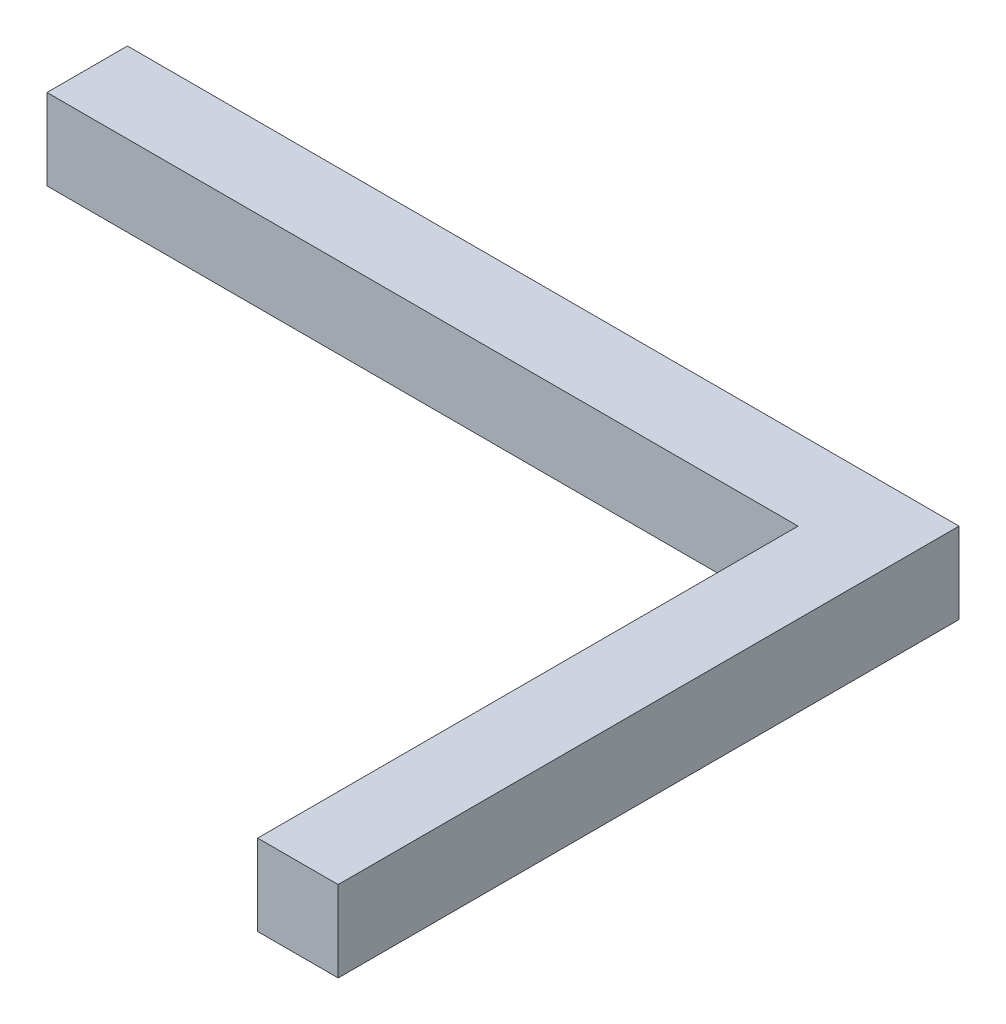
SolidWorks part; units mm, degrees
ref_plane "Front Plane" through (0, 0, 0) normal (0, 0, 1) x (1, 0, 0)
ref_plane "Top Plane" through (0, 0, 0) normal (0, 1, 0) x (1, 0, 0)
ref_plane "Right Plane" through (0, 0, 0) normal (1, 0, 0) x (0, 0, -1)
sketch "Sketch1" plane through (0, 0, 0) normal (0, 1, 0) x (1, 0, 0)
  line L1 (0, 0) -> (49.6, 0)
  line L2 (0, 0) -> (0, 49.6)
  line L3 (0, 49.6) -> (49.6, 49.6)
  line L4 (49.6, 0) -> (49.6, 49.6)
  line L5 (0, 0) -> (49.6, 49.6) construction
  line L6 (0, 49.6) -> (49.6, 0) construction
  point P4 (24.8, 24.8)
  dimension "D1" = 49.6
  dimension "D2" = 49.6
extrude "Boss-Extrude1" add sketch "Sketch1" along normal blind 4.826
sketch "Sketch2" plane through (0, 4.826, 0) normal (0, 1, 0) x (1, 0, 0)
  line L5 (8.1217, 49.6) -> (8.1217, 44.8) construction
  line L6 (0, 0) -> (44.8, 0)
  line L7 (0, 0) -> (0, 44.8)
  line L9 (0, 44.8) -> (44.8, 44.8)
  line L11 (44.8, 0) -> (44.8, 44.8)
  line L12 (0, 0) -> (44.8, 44.8) construction
  line L13 (0, 44.8) -> (44.8, 0) construction
  line L14 (49.6, 49.6) -> (0, 49.6) construction
  point P4 (22.4, 22.4)
  dimension "D1" = 4.8
  dimension "D2" = 44.8
extrude "Cut-Extrude1" cut sketch "Sketch2" against normal through all
ref_plane "Plane1" through (0, 2.413, 0) normal (0, -1, 0) x (-1, 0, 0)
ref_plane "Plane2" through (0, 0, -24.8) normal (0, 0, -1) x (-1, 0, 0)
ref_plane "Plane3" through (0, 0, -47.2) normal (0, 0, 1) x (1, 0, 0)
ref_point "Point1"
ref_plane "Plane5" through (47.2, 0, 0) normal (1, 0, 0) x (0, 0, -1)
ref_plane "Plane6" through (0, 2.413, 0) normal (0, 1, 0) x (1, 0, 0)
sketch "Sketch6" plane through (49.6, 0, 0) normal (1, 0, 0) x (0, 0, -1)
  line L1 (0, 0) -> (49.6, 0) construction
  line L2 (0, 4.826) -> (12.57, 4.826)
  line L3 (0, 4.826) -> (0, 0)
  line L4 (0, 0) -> (12.57, 0)
  line L5 (12.57, 4.826) -> (12.57, 0)
  line L6 (0, 4.826) -> (12.57, 0) construction
  line L7 (0, 0) -> (12.57, 4.826) construction
  line L8 (12.57, 15.113) -> (12.57, -10.287) construction
  point P8 (6.285, 2.413)
extrude "Cut-Extrude2" cut sketch "Sketch6" against normal through all
ref_point "Point3"
equation "\"MDF\"= 4.8mm"
equation "\"Foamcore\"= 4.6mm"
equation "\"GMaterial\"= \"MDF\""
equation "\"PCB\" = 1.6mm"
equation "\"BaseWidth\" = 10in"
equation "\"SkidLength\" = 1in"
equation "\"SkidClearance\" = 0.4in"
equation "\"MotorMountLength\" = 2in"
equation "\"MotorMountWidth\" = \"GMaterial\""
equation "\"MotorMountHeight\" = 2.25in"
equation "\"UnoStackWidth\" = 77.4mm"
equation "\"UnoStackLength\" = 79.8mm"
equation "\"UnoStackHeight\" = 34.2mm"
equation "\"TallHexRiserHeight\" = 22.2mm"
equation "\"PingPongBallSize\" = 40mm"
equation "\"BarrelLength\" = 9in"
equation "\"BarrelSize\" = \"PingPongBallSize\""
equation "\"PlatformLength\" = 4in"
equation "\"PlatformWidth\" = 6in"
equation "\"WheelDiameter\"=2.99213"
equation "\"ServoMountHeight\"=2.49223"
equation "\"ServoGearHeight\" = 0.95330261in"
equation "\"ServoMountLength\"= 1.53774"
equation "\"PivotHoleRadius\"= 0.616358"
equation "\"PlatformMountHeight\" = 3.19"
equation "\"TensionOffSet\"= .3mm"
equation "\"MotorMountWedge\"=0.333333"
equation "\"LaserCutterOffset\"= .3mm"
equation "\"BumperWidth\"=11"
equation "\"PitcherWheelCompression\" = 2.5mm"
equation "\"PitchingWheelWidth\" = 26.2mm"
equation "\"PitchingWheelDiameter\" = 65.5mm"
equation "\"PitchingWheelMountOffset\" = 8.4mm"
equation "\"PitchingWheelInnerDiameter\" = 45.5mm"
equation "\"PitchingWheelBoltShoulder\" = 4.5mm"
equation "\"BrassCouplingLength\" = 18mm"
equation "\"PitchingMotorHeight\" = 57.0mm"
equation "\"PitchingMotorShaftTopHeight\" = \"PitchingMotorHeight\" - 44.1mm"
equation "\"PitchingMotorBodyHeight\" = 38mm"
equation "\"PitchingMotorTopShoulderHeight\" = 40.6mm - \"PitchingMotorBodyHeight\" "
equation "\"PitchingMotorBottomShoulderHeight\" = 40.2mm - \"PitchingMotorBodyHeight\""
equation "\"PitchingMotorBottomShaftHeight\" = \"PitchingMotorHeight\" - \"PitchingMotorShaftTopHeight\" - \"PitchingMotorTopShoulderHeight\" - \"PitchingMotorBodyHeight\" - \"PitchingMotorBottomShoulderHeight\""
equation "\"PitchingMotorShaftDiameter\" = 2.2mm"
equation "\"PitchingMotorBodyDiameter\" = 27.4mm"
equation "\"PitchingMotorTopShoulderDiameter\" = 9.8mm"
equation "\"PitchingMotorBottomShoulderDiameter\" = 9.8mm"
equation "\"BrassCouplingHexSize\" = 12mm"
equation "\"BrassCouplingBoreSize\" = 3.17mm"
equation "\"PitchingMotorMountingHoleDistance\" = 16mm"
equation "\"Acrylic\" = 4.4mm"
equation "\"PitchingMotorDistance\" = \"PitchingWheelDiameter\" + \"PingPongBallSize\" - \"PitcherWheelCompression\"*2"
equation "\"PitchingMotorPlatformOffset\"=1"
equation "\"ServoPlatformOffset\"=1.64173"
equation "\"BallBearingDiameter\" = 22mm"
equation "\"BallBearingWidth\" = 9mm"
equation "\"BallBearingHexShoulder\" = 9mm - 5.9mm"
equation "\"BallBearingHexSize\" = .36in"
equation "\"PlatformMountFootLength\"=0.857143"
equation "\"WheelWidth\"= 26mm"
equation "\"ServoMountReductionBackHeight\"=2.25"
equation "\"PlatformBottomWidthThird\" =  0.857143in"
equation "\"PlatformMountBackReductionHeight\"= 2.5in"
equation "\"PlatformMountBackReductionWidth\"= 3/7in"
equation "\"PlatformMountFrontReductionWidth\" =  1.46226in"
equation "\"PlatformMountFrontReductionHeight\" = 2.5in"
equation "\"D1@Sketch1\"=\"PingPongBallSize\"+\"MDF\"*2"
equation "\"D2@Sketch1\"=\"PingPongBallSize\" + \"MDF\"*2"
equation "\"D1@Sketch2\"=\"MDF\""
equation "\"D2@Sketch2\"=\"PingPongBallSize\"+\"MDF\""
